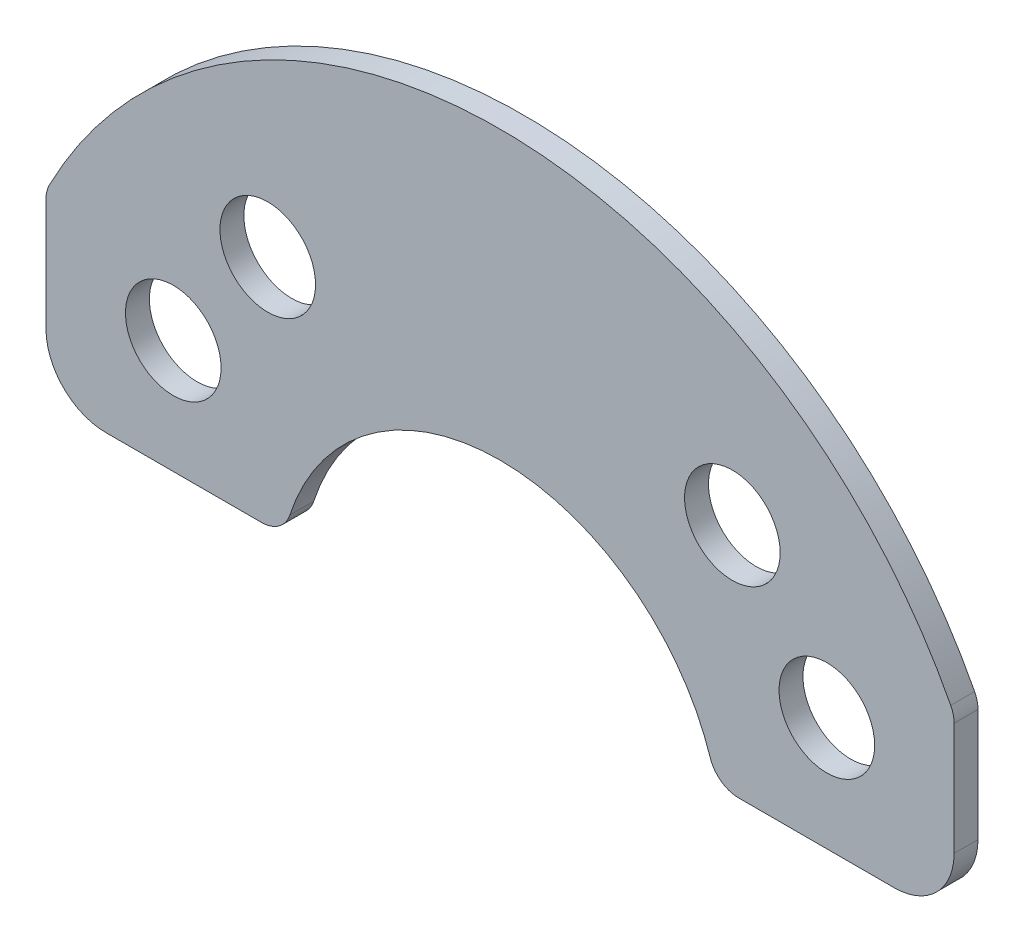
SolidWorks part; units mm, degrees
ref_plane "Front Plane" through (0, 0, 0) normal (0, 0, 1) x (1, 0, 0)
ref_plane "Top Plane" through (0, 0, 0) normal (0, 1, 0) x (1, 0, 0)
ref_plane "Right Plane" through (0, 0, 0) normal (1, 0, 0) x (0, 0, -1)
sketch "Sketch1" plane through (0, 0, 0) normal (0, 0, 1) x (1, 0, 0)
  line L0 (-38, 4) -> (-18.0624, 4)
  line L1 (-38, 4) -> (-38, 19.0329)
  line L2 (38, 4) -> (38, 19.0329)
  line L3 (0, 4) -> (0, 0) construction
  line L4 (18.0624, 4) -> (38, 4)
  line L5 (-18.0624, 4) -> (18.0624, 4) construction
  arc A0 (38, 19.0329) -> (-38, 19.0329) centre (0, 0) ccw
  arc A1 (18.0624, 4) -> (-18.0624, 4) centre (0, 0) ccw
  point P5 (0, 0)
  point P10 (-18.0624, 4)
  dimension "D1" = 85
  dimension "D4" = 37
  dimension "D2" = 4
  dimension "D3" = 76
extrude "Boss-Extrude1" add sketch "Sketch1" along normal mid plane 2
sketch "Sketch2" plane through (0, 0, 1) normal (0, 0, 1) x (1, 0, 0)
  line L0 (-27.3496, 13.5) -> (27.3496, 13.5) construction
  line L1 (-38, 4) -> (-18.0624, 4) construction
  line L2 (-19.4422, 23.5) -> (19.4422, 23.5) construction
  circle A0 centre (0, 0) radius 26.5 construction
  circle A1 centre (0, 0) radius 34.5 construction
  circle A2 centre (-27.3496, 13.5) radius 4
  circle A3 centre (-19.4422, 23.5) radius 4
  circle A4 centre (19.4422, 23.5) radius 4
  circle A5 centre (27.3496, 13.5) radius 4
  point P14 (-18.6823, 24.1086)
  dimension "D1" = 53
  dimension "D2" = 8
  dimension "D3" = 9.5
  dimension "D4" = 10
extrude "Cut-Extrude1" cut sketch "Sketch2" against normal through all
fillet "Fillet1" radius 5 2 edges at (38, 4, 0) (-38, 4, 0)
fillet "Fillet2" radius 2.5 4 edges at (-38, 19.0329, 0) (-18.0624, 4, 0) (38, 19.0329, 0) (18.0624, 4, 0)
